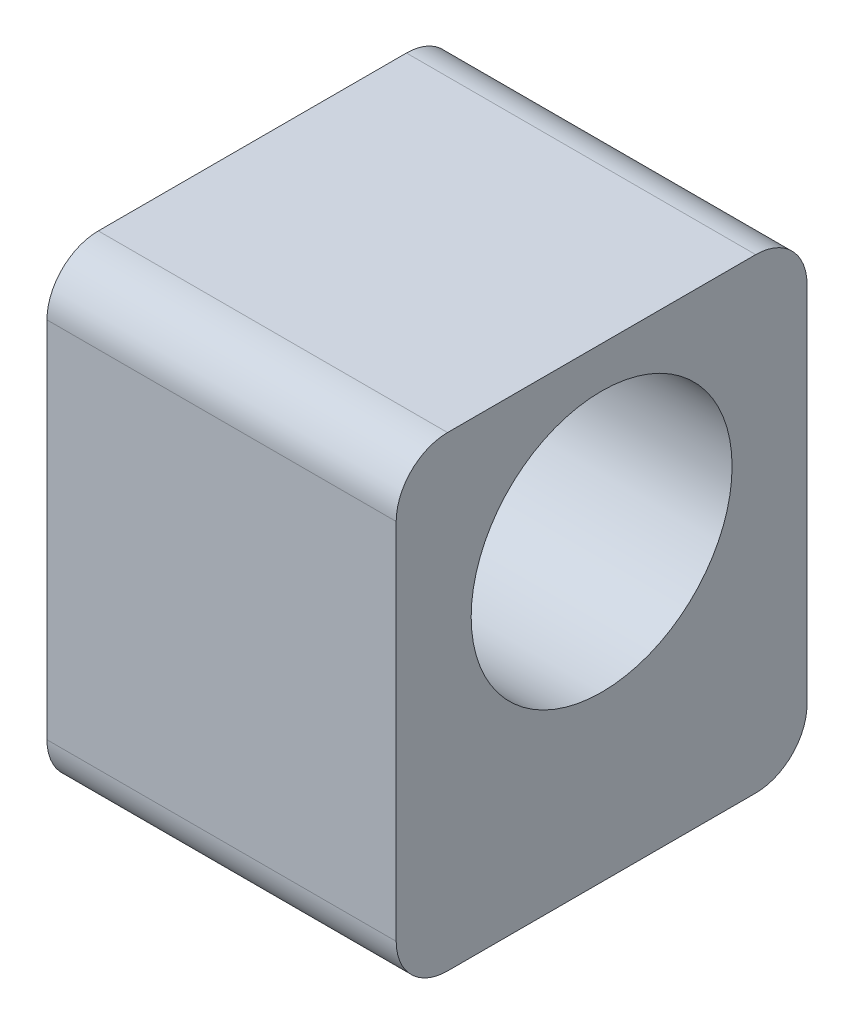
SolidWorks part; units mm, degrees
ref_plane "Front Plane" through (0, 0, 0) normal (0, 0, 1) x (1, 0, 0)
ref_plane "Top Plane" through (0, 0, 0) normal (0, 1, 0) x (1, 0, 0)
ref_plane "Right Plane" through (0, 0, 0) normal (1, 0, 0) x (0, 0, -1)
sketch "Sketch1" plane through (0, 0, 0) normal (1, 0, 0) x (0, 0, -1)
  line L0 (-15, -28.7) -> (15, -28.7)
  line L1 (20, -23.7) -> (20, 11.7)
  line L2 (15, 16.7) -> (-15, 16.7)
  line L3 (-20, 11.7) -> (-20, -23.7)
  arc A0 (15, -28.7) -> (20, -23.7) centre (15, -23.7) ccw
  arc A1 (20, 11.7) -> (15, 16.7) centre (15, 11.7) ccw
  arc A2 (-15, 16.7) -> (-20, 11.7) centre (-15, 11.7) ccw
  arc A3 (-20, -23.7) -> (-15, -28.7) centre (-15, -23.7) ccw
  circle A4 centre (0, 0) radius 12.7
extrude "Boss-Extrude1" add sketch "Sketch1" along normal mid plane 34
